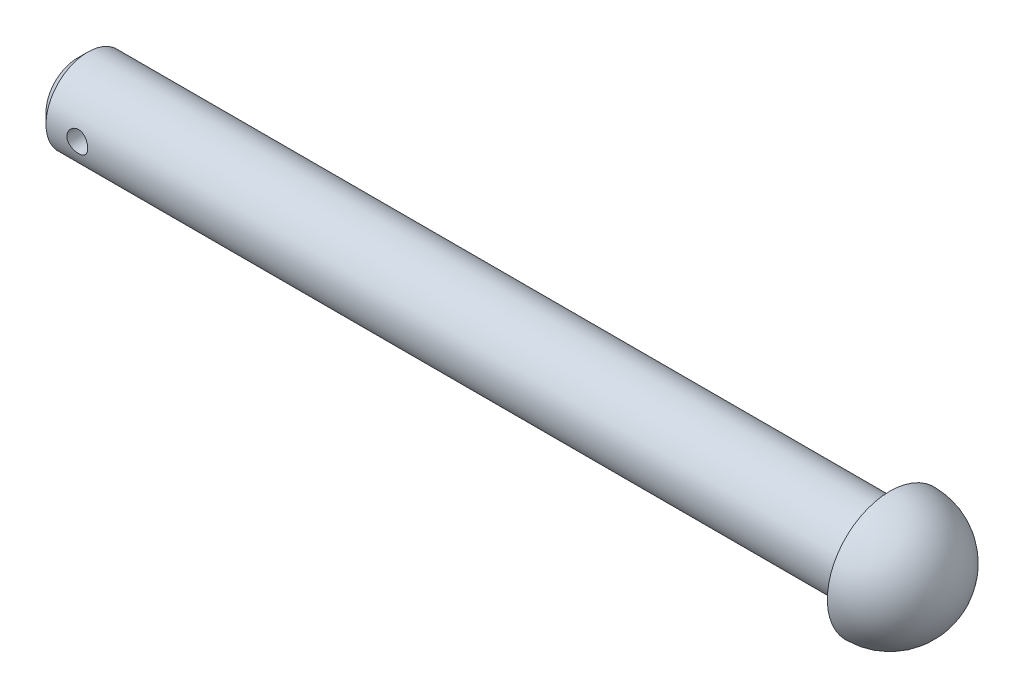
SolidWorks part; units mm, degrees
ref_plane "Front Plane" through (0, 0, 0) normal (0, 0, 1) x (1, 0, 0)
ref_plane "Top Plane" through (0, 0, 0) normal (0, 1, 0) x (1, 0, 0)
ref_plane "Right Plane" through (0, 0, 0) normal (1, 0, 0) x (0, 0, -1)
sketch "Sketch1" plane through (0, 0, 0) normal (0, 0, 1) x (1, 0, 0)
  line L0 (0, 0) -> (0, 2)
  line L1 (0, 2) -> (39, 2)
  line L2 (39, 2) -> (39, 3)
  line L3 (42, 0) -> (0, 0)
  arc A0 (39, 3) -> (42, 0) centre (39, 0) cw
  point P7 (0, 0)
  dimension "D2" = 3
  dimension "D1" = 2
  dimension "D3" = 39
revolve "Revolve1" add sketch "Sketch1" angle 360 about L3
sketch "Sketch2" plane through (0, 0, 0) normal (0, 0, 1) x (1, 0, 0)
  line L0 (39, 3) -> (39, -3) construction
  circle A0 centre (2, 0) radius 0.5
  point P4 (0, 0)
  dimension "D1" = 1
  dimension "D2" = 37
extrude "Cut-Extrude1" cut sketch "Sketch2" against normal mid plane 10
chamfer "Chamfer1" distance 0.5 angle 45 1 edges at (0, 2, 0)
